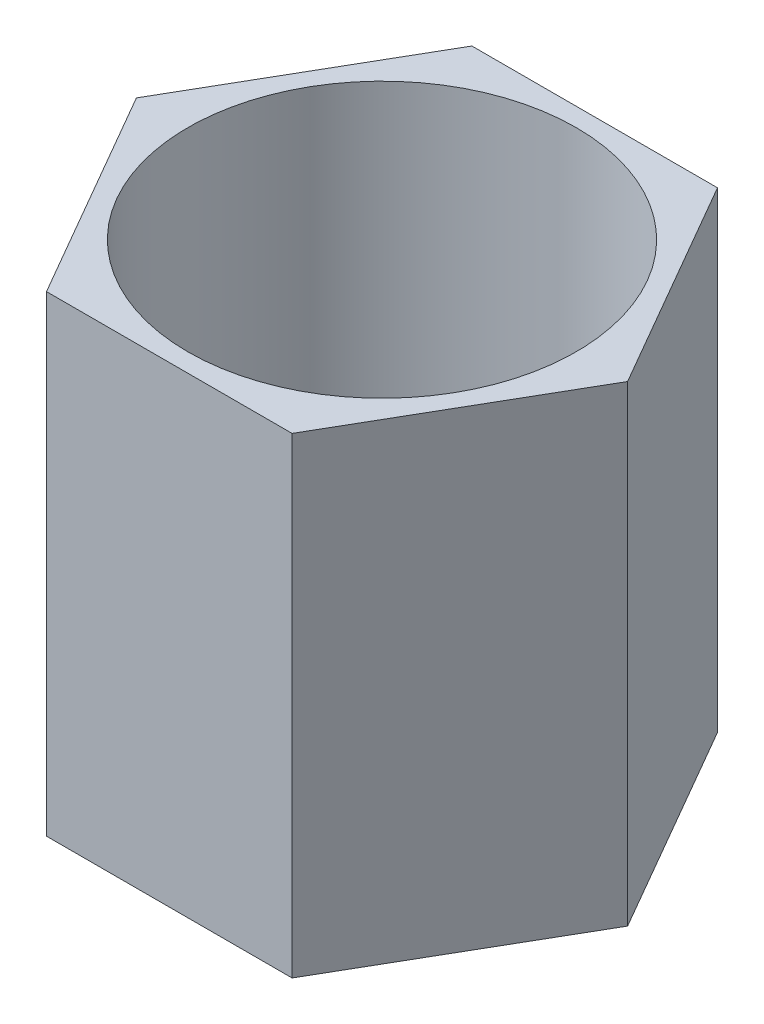
SolidWorks part; units mm, degrees
ref_plane "Front Plane" through (0, 0, 0) normal (0, 0, 1) x (1, 0, 0)
ref_plane "Top Plane" through (0, 0, 0) normal (0, 1, 0) x (1, 0, 0)
ref_plane "Right Plane" through (0, 0, 0) normal (1, 0, 0) x (0, 0, -1)
sketch "Sketch1" plane through (0, 0, 0) normal (0, 1, 0) x (1, 0, 0)
  circle A0 centre (0, 0) radius 3.575
  circle A1 centre (0, 0) radius 2.1
  dimension "D1" = 7.15
  dimension "D2" = 4.2
extrude "Boss-Extrude1" add sketch "Sketch1" along normal blind 5.1
sketch "Sketch2" plane through (0, 5.1, 0) normal (0, 1, 0) x (1, 0, 0)
  line L1 (1.3279, 2.3) -> (-1.3279, 2.3)
  line L2 (-1.3279, 2.3) -> (-2.6558, 0)
  line L3 (-2.6558, 0) -> (-1.3279, -2.3)
  line L4 (-1.3279, -2.3) -> (1.3279, -2.3)
  line L5 (1.3279, -2.3) -> (2.6558, 0)
  line L6 (2.6558, 0) -> (1.3279, 2.3)
  circle A0 centre (0, 0) radius 2.3 construction
  circle A1 centre (0, 0) radius 3.575 construction
  circle A2 centre (0, 0) radius 3.575
  dimension "D1" = 4.6
extrude "Cut-Extrude1" cut sketch "Sketch2" against normal blind 10
